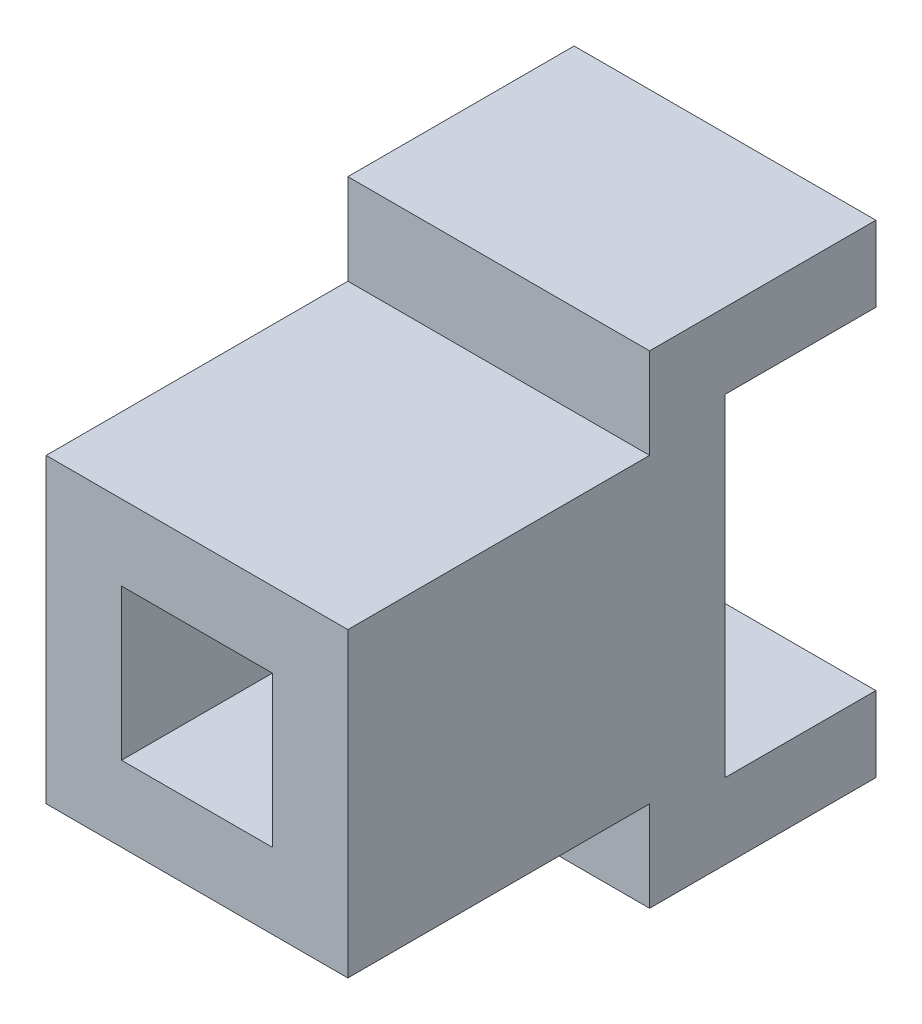
SolidWorks part; units mm, degrees
ref_plane "前视基准面" through (0, 0, 0) normal (0, 0, 1) x (1, 0, 0)
ref_plane "上视基准面" through (0, 0, 0) normal (0, 1, 0) x (1, 0, 0)
ref_plane "右视基准面" through (0, 0, 0) normal (1, 0, 0) x (0, 0, -1)
sketch "草图1" plane through (0, 0, 0) normal (0, 0, 1) x (1, 0, 0)
  line L1 (0, 0) -> (20, 0)
  line L2 (0, 0) -> (0, 20)
  line L3 (0, 20) -> (20, 20)
  line L4 (20, 0) -> (20, 20)
  dimension "D1" = 20
  dimension "D2" = 20
extrude "凸台-拉伸1" add sketch "草图1" along normal blind 20
sketch "草图3" plane through (0, 0, 0) normal (0, 0, -1) x (-1, 0, 0)
  line L0 (-20, 20) -> (0, 20) construction
  line L1 (-5, 15) -> (-15, 15)
  line L2 (-5, 15) -> (-5, 5)
  line L3 (-5, 5) -> (-15, 5)
  line L4 (-15, 15) -> (-15, 5)
  line L5 (-20, 0) -> (-20, 20) construction
  line L6 (0, 0) -> (-20, 0) construction
  line L7 (0, 20) -> (0, 0) construction
  point P10 (-10, 0)
  dimension "D1" = 5
  dimension "D2" = 5
  dimension "D3" = 5
  dimension "D4" = 5
extrude "切除-拉伸1" cut sketch "草图3" against normal blind 20
sketch "草图4" plane through (0, 0, 0) normal (0, 0, -1) x (-1, 0, 0)
  line L0 (0, 0) -> (-20, 0) construction
  line L1 (-20, -6) -> (0, -6)
  line L2 (-20, -6) -> (-20, 26)
  line L3 (-20, 26) -> (0, 26)
  line L4 (0, -6) -> (0, 26)
  line L5 (-15, 15) -> (-15, 5) construction
  point P4 (-10, -6)
  dimension "D1" = 32
  dimension "D2" = 6
  dimension "D3" = 20
  dimension "D4" = 5
extrude "凸台-拉伸2" add sketch "草图4" along normal blind 15
sketch "草图5" plane through (0, 0, -15) normal (0, 0, -1) x (-1, 0, 0)
  line L0 (-20, 26) -> (-20, -6) construction
  line L1 (-20, -1) -> (0, -1)
  line L2 (-20, -1) -> (-20, 21)
  line L3 (-20, 21) -> (0, 21)
  line L4 (0, -1) -> (0, 21)
  line L5 (0, -6) -> (0, 26) construction
  line L6 (-20, -6) -> (0, -6) construction
  dimension "D1" = 22
  dimension "D2" = 5
extrude "切除-拉伸2" cut sketch "草图5" against normal blind 10
